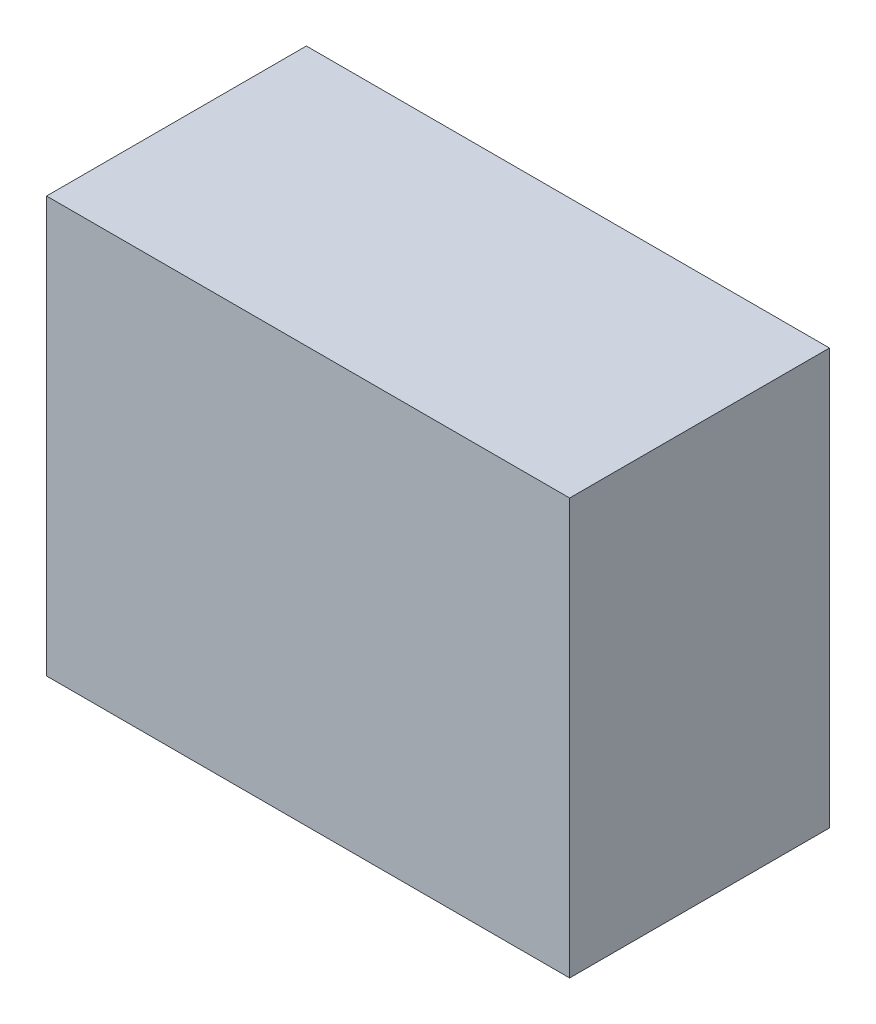
SolidWorks part; units mm, degrees
ref_plane "前视基准面" through (0, 0, 0) normal (0, 0, 1) x (1, 0, 0)
ref_plane "上视基准面" through (0, 0, 0) normal (0, 1, 0) x (1, 0, 0)
ref_plane "右视基准面" through (0, 0, 0) normal (1, 0, 0) x (0, 0, -1)
other "Configuration Table"
ref_plane "基准面1" through (0, 0, 0) normal (0, 0, -1) x (-1, 0, 0)
sketch "草图1" plane through (0, 0, 0) normal (0, 0, -1) x (-1, 0, 0)
  line L0 (75.5, 60) -> (-75.5, 60)
  line L1 (-75.5, 60) -> (-75.5, -60)
  line L2 (-75.5, -60) -> (75.5, -60)
  line L3 (75.5, -60) -> (75.5, 60)
  dimension "D1" = 120
  dimension "D2" = 151
extrude "凸台-拉伸1" add sketch "草图1" against normal blind 75
